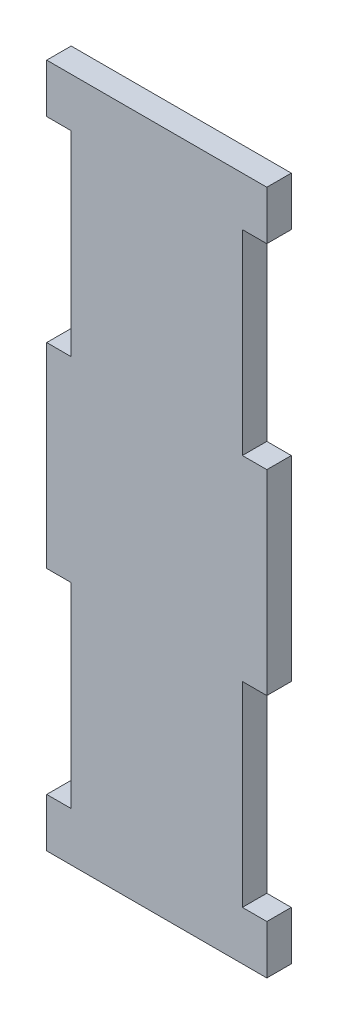
SolidWorks part; units mm, degrees
ref_plane "Plan de face" through (0, 0, 0) normal (0, 0, 1) x (1, 0, 0)
ref_plane "Plan de dessus" through (0, 0, 0) normal (0, 1, 0) x (1, 0, 0)
ref_plane "Plan de droite" through (0, 0, 0) normal (1, 0, 0) x (0, 0, -1)
sketch "Esquisse1" plane through (0, 0, 0) normal (0, 0, 1) x (1, 0, 0)
  line L0 (45, 280) -> (45, 0) construction
  line L1 (0, 0) -> (90, 0)
  line L2 (0, 0) -> (0, 280) construction
  line L3 (0, 280) -> (90, 280)
  line L4 (90, 0) -> (90, 280) construction
  line L5 (0, 0) -> (0, 20)
  line L6 (0, 20) -> (10, 20)
  line L7 (10, 20) -> (10, 100)
  line L8 (10, 100) -> (0, 100)
  line L9 (0, 100) -> (0, 180)
  line L10 (0, 180) -> (10, 180)
  line L11 (10, 180) -> (10, 260)
  line L12 (10, 260) -> (0, 260)
  line L13 (0, 260) -> (0, 280)
  line L14 (10, 260) -> (10, 280) construction
  line L15 (10, 180) -> (10, 100) construction
  line L16 (10, 20) -> (10, 0) construction
  line L17 (90, 0) -> (90, 20)
  line L18 (90, 20) -> (80, 20)
  line L19 (80, 20) -> (80, 100)
  line L20 (80, 100) -> (90, 100)
  line L21 (90, 100) -> (90, 180)
  line L22 (90, 180) -> (80, 180)
  line L23 (80, 180) -> (80, 260)
  line L24 (80, 260) -> (90, 260)
  line L25 (90, 260) -> (90, 280)
  dimension "D1" = 80
  dimension "D2" = 80
  dimension "D3" = 20
  dimension "D4" = 20
  dimension "D5" = 80
  dimension "D6" = 10
  dimension "D7" = 45
extrude "Boss.-Extru.1" add sketch "Esquisse1" along normal blind 10
